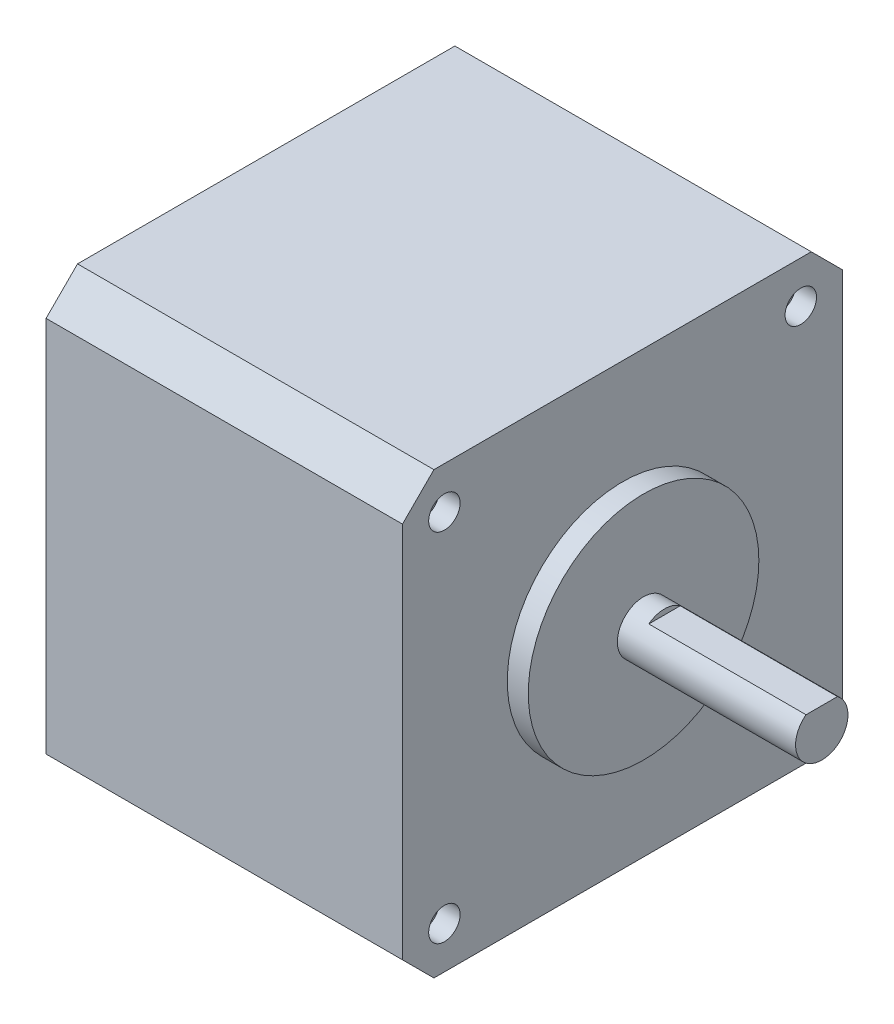
SolidWorks part; units mm, degrees
ref_plane "Front Plane" through (0, 0, 0) normal (0, 0, 1) x (1, 0, 0)
ref_plane "Top Plane" through (0, 0, 0) normal (0, 1, 0) x (1, 0, 0)
ref_plane "Right Plane" through (0, 0, 0) normal (1, 0, 0) x (0, 0, -1)
sketch "Sketch1" plane through (0, 0, 0) normal (0, 1, 0) x (1, 0, 0)
  line L1 (17, -21) -> (-17, -21)
  line L2 (17, -21) -> (17, 21)
  line L3 (17, 21) -> (-17, 21)
  line L4 (-17, -21) -> (-17, 21)
  line L5 (17, -21) -> (-17, 21) construction
  line L6 (17, 21) -> (-17, -21) construction
  point P0 (0, 0)
  dimension "D1" = 34
  dimension "D2" = 42
extrude "Boss-Extrude1" add sketch "Sketch1" along normal blind 42
sketch "Sketch2" plane through (17, 0, 0) normal (1, 0, 0) x (0, 0, -1)
  line L0 (-21, 0) -> (21, 0) construction
  line L1 (-21, 42) -> (-21, 0) construction
  circle A0 centre (0, 21) radius 11
  dimension "D2" = 21
  dimension "D3" = 22
  dimension "D1" = 21
extrude "Boss-Extrude2" add sketch "Sketch2" along normal blind 2
sketch "Sketch3" plane through (19, 0, 0) normal (1, 0, 0) x (0, 0, -1)
  circle A0 centre (0, 21) radius 2.5
  circle A1 centre (0, 21) radius 11 construction
  dimension "D1" = 5
extrude "Boss-Extrude3" add sketch "Sketch3" along normal blind 2
sketch "Sketch4" plane through (21, 0, 0) normal (1, 0, 0) x (0, 0, -1)
  line L0 (1.5, 23) -> (-1.5, 23)
  circle A1 centre (0, 21) radius 2.5
  arc A2 (-1.5, 23) -> (1.5, 23) centre (0, 21) ccw
  dimension "D2" = 2
  dimension "D1" = 0
extrude "Boss-Extrude4" add sketch "Sketch4" along normal blind 15
chamfer "Chamfer1" distance 3 angle 45 4 edges at (0, 42, -21) (0, 0, -21) (0, 0, 21) (0, 42, 21)
sketch "Sketch5" plane through (17, 0, 0) normal (1, 0, 0) x (0, 0, -1)
  line L1 (17, 4) -> (-17, 4) construction
  line L2 (17, 4) -> (17, 38) construction
  line L3 (17, 38) -> (-17, 38) construction
  line L4 (-17, 4) -> (-17, 38) construction
  line L5 (17, 4) -> (-17, 38) construction
  line L6 (17, 38) -> (-17, 4) construction
  circle A0 centre (-17, 38) radius 1.5
  circle A1 centre (-17, 4) radius 1.5
  circle A2 centre (17, 4) radius 1.5
  circle A3 centre (17, 38) radius 1.5
  point P0 (0, 21)
  dimension "D2" = 3
  dimension "D1" = 34
extrude "Cut-Extrude1" cut sketch "Sketch5" against normal blind 2
mirror "Mirror1" about plane through (0, 0, 0) normal (1, 0, 0) of "Cut-Extrude1"
